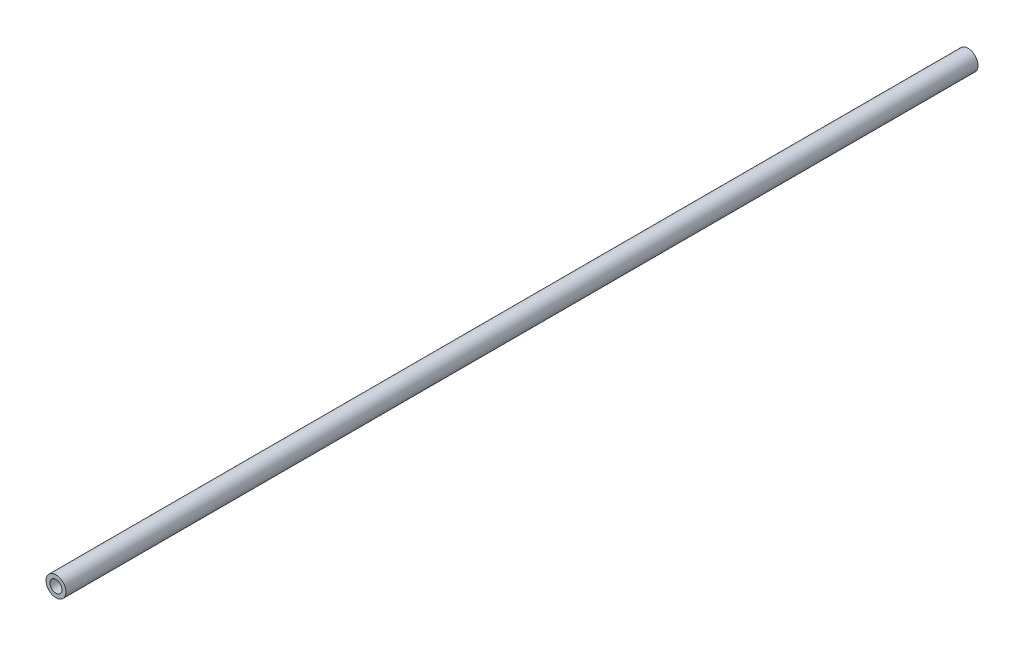
SolidWorks part; units mm, degrees
material "3.0205 (EN-AW 1200)"
ref_plane "前视基准面" through (0, 0, 0) normal (0, 0, 1) x (1, 0, 0)
ref_plane "上视基准面" through (0, 0, 0) normal (0, 1, 0) x (1, 0, 0)
ref_plane "右视基准面" through (0, 0, 0) normal (1, 0, 0) x (0, 0, -1)
sketch "草图1" plane through (0, 0, 0) normal (0, 0, 1) x (1, 0, 0)
  circle A0 centre (0, 0) radius 3
  circle A1 centre (0, 0) radius 5
extrude "凸台-拉伸1" add sketch "草图1" along normal blind 457.5
equation "\"462.5.00mm\"=10"
